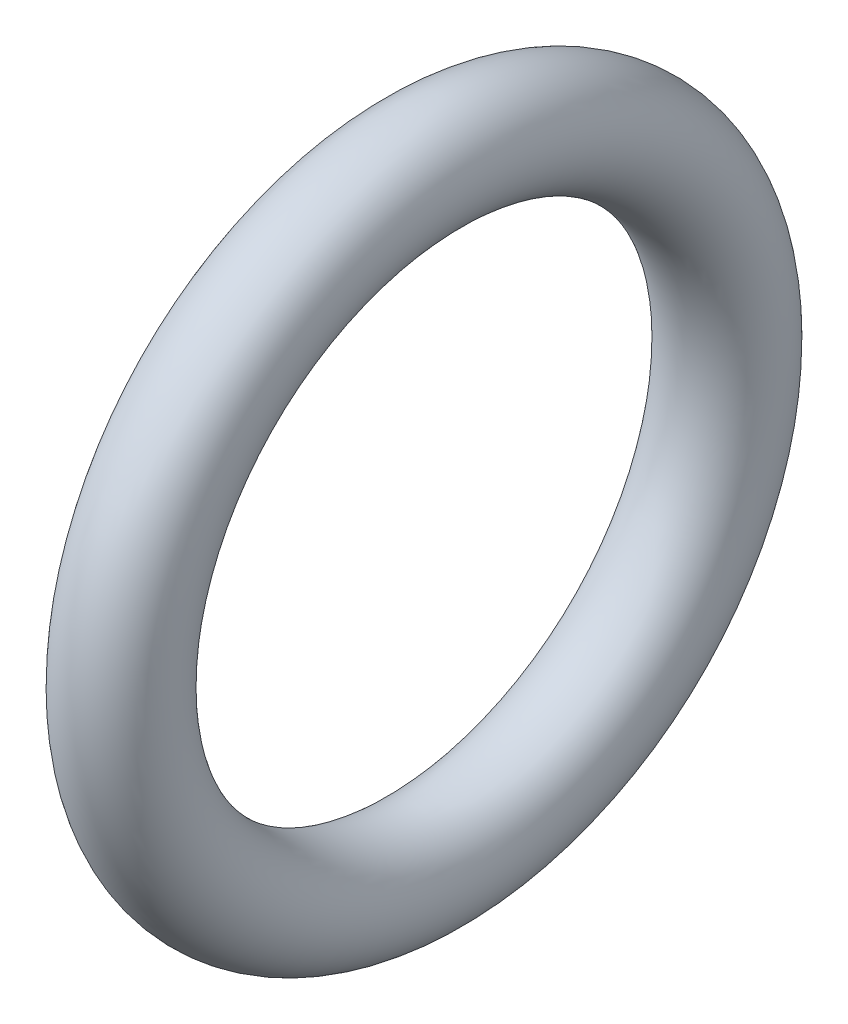
SolidWorks part; units mm, degrees
ref_plane "Front Plane" through (0, 0, 0) normal (0, 0, 1) x (1, 0, 0)
ref_plane "Top Plane" through (0, 0, 0) normal (0, 1, 0) x (1, 0, 0)
ref_plane "Right Plane" through (0, 0, 0) normal (1, 0, 0) x (0, 0, -1)
sketch "Sketch4" plane through (0, 0, 0) normal (0, 0, 1) x (1, 0, 0)
  line L0 (0, 0) -> (11.9586, 0) construction
  line L1 (0, 0) -> (0, 5.425) construction
  circle A0 centre (0, 5.425) radius 0.95
  point P5 (-0.95, 5.425)
  point P6 (0, 6.375)
  point P7 (0.95, 5.425)
  point P8 (0, 4.475)
  dimension "D1" = 1.9
  dimension "D2" = 5.425
revolve "Revolve1" add sketch "Sketch4" angle 360 about L0
